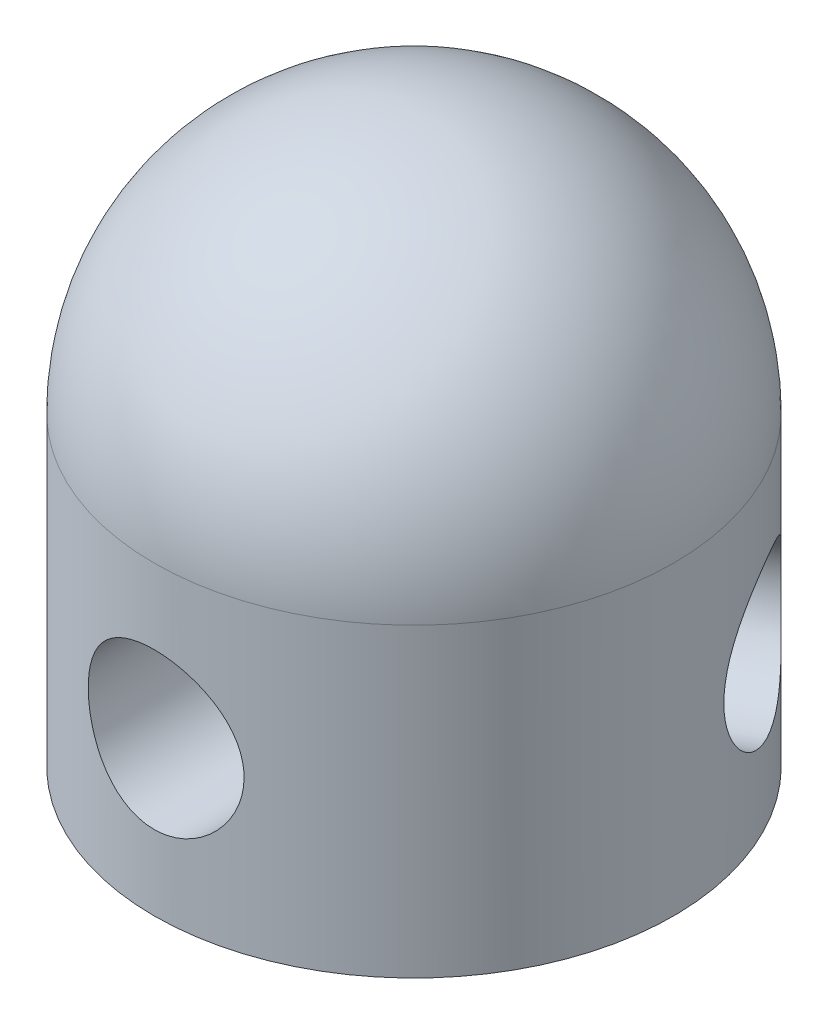
SolidWorks part; units mm, degrees
ref_plane "Front Plane" through (0, 0, 0) normal (0, 0, 1) x (1, 0, 0)
ref_plane "Top Plane" through (0, 0, 0) normal (0, 1, 0) x (1, 0, 0)
ref_plane "Right Plane" through (0, 0, 0) normal (1, 0, 0) x (0, 0, -1)
sketch "cirkel" plane through (0, 0, 0) normal (0, 1, 0) x (1, 0, 0)
  circle A0 centre (0, 0) radius 17
  dimension "D1" = 34
extrude "cilinder" add sketch "cirkel" along normal blind 20
sketch "boog" plane through (0, 0, 0) normal (0, 0, 1) x (1, 0, 0)
  line L0 (0, 20) -> (0, 37)
  line L1 (17, 20) -> (-17, 20) construction
  line L4 (0, 20) -> (-17, 20)
  arc A1 (-17, 20) -> (0, 37) centre (0, 20) cw
revolve "bol" add sketch "boog" angle 360 about L0
ref_plane "Plane1" through (0, 0, 17) normal (0, 0, 1) x (1, 0, 0)
sketch "cirkel_gat" plane through (0, 0, 17) normal (0, 0, 1) x (1, 0, 0)
  line L0 (-17, 0) -> (17, 0) construction
  line L1 (0, 0) -> (0, 10) construction
  circle A0 centre (0, 10) radius 5.1
  dimension "D1" = 10.2
  dimension "D2" = 10
extrude "opening" cut sketch "cirkel_gat" against normal blind 10 contours A0
pattern_circular "gaten_patroon" count 3 over 360 about axis through (0, 0, 0) along (0, 1, 0) of "opening"
sketch "cirkel1" plane through (0, 0, 0) normal (0, -1, 0) x (-1, 0, 0)
  circle A0 centre (0, 0) radius 13.5
  dimension "D1" = 27
extrude "opening_opzet" cut sketch "cirkel1" against normal blind 3
sketch "cirkel2" plane through (0, 3, 0) normal (0, -1, 0) x (-1, 0, 0)
  circle A0 centre (0, 0) radius 2
  dimension "D1" = 4
extrude "gat_verloopstuk" cut sketch "cirkel2" against normal blind 8
sketch "cirkel3" plane through (0, 3, 0) normal (0, -1, 0) x (1, 0, 0)
  circle A0 centre (0, 0) radius 3
  dimension "D1" = 6
extrude "gat_verloopstuk_rand" cut sketch "cirkel3" against normal blind 2
